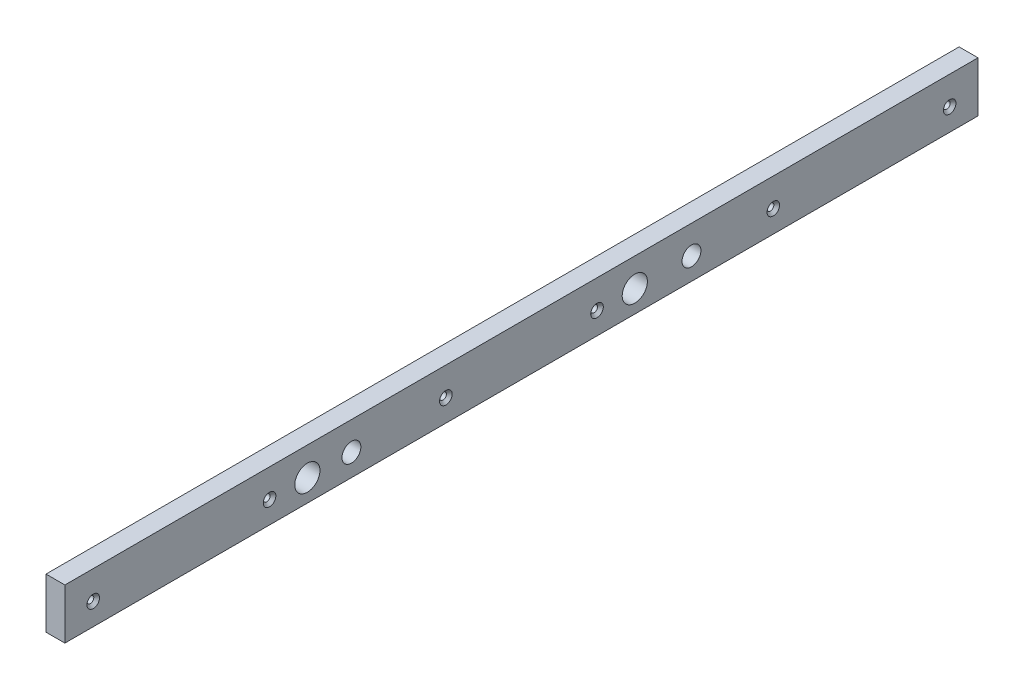
SolidWorks part; units mm, degrees
material "6061-T6 (SS)"
ref_plane "Front Plane" through (0, 0, 0) normal (0, 0, 1) x (1, 0, 0)
ref_plane "Top Plane" through (0, 0, 0) normal (0, 1, 0) x (1, 0, 0)
ref_plane "Right Plane" through (0, 0, 0) normal (1, 0, 0) x (0, 0, -1)
sketch "Sketch1" plane through (0, 0, 0) normal (0, 0, 1) x (1, 0, 0)
  line L0 (4.7625, 12.7) -> (-4.7625, -12.7) construction
  line L1 (-4.7625, 12.7) -> (4.7625, 12.7)
  line L2 (-4.7625, 12.7) -> (-4.7625, -12.7)
  line L3 (-4.7625, -12.7) -> (4.7625, -12.7)
  line L4 (4.7625, 12.7) -> (4.7625, -12.7)
  dimension "D1" = 25.4
  dimension "D2" = 9.525
extrude "Boss-Extrude1" add sketch "Sketch1" along normal mid plane 460.375
sketch "Sketch2" plane through (4.7625, 0, 0) normal (1, 0, 0) x (0, 0, -1)
  circle A1 centre (-107.95, -1.5875) radius 6.35
  circle A2 centre (57.15, -1.5875) radius 6.35
  point P0 (-25.4, -1.5875)
  dimension "D1" = 12.7
  dimension "D5" = 165.1
  dimension "D2" = 57.15
  dimension "D4" = 1.5875
  dimension "D6" = 82.55
  dimension "D7" = 25.4
extrude "Cut-Extrude1" cut sketch "Sketch2" against normal up to next
hole_wizard "3/8 (0.375) Diameter Hole1" positions "Sketch4" profile "Sketch3" hole size "3/8" standard "Ansi Inch" end condition through all
sketch "Sketch4" plane through (-4.7625, 0, 0) normal (-1, 0, 0) x (0, 0, 1)
  point P0 (85.725, -1.5875)
  point P1 (-85.725, -1.5875)
  dimension "D1" = 85.725
  dimension "D2" = 85.725
  dimension "D3" = 1.5875
sketch "Sketch3" plane through (-4.7625, -1.5875, 85.725) normal (0, 1, 0) x (0, 0, 1)
  line L0 (0, 0) -> (0, 9.525)
  line L1 (0, 9.525) -> (4.7625, 9.525)
  line L2 (4.7625, 9.525) -> (4.7625, 0)
  line L5 (4.7625, 0) -> (0, 0)
  line L11 (0, -6.35) -> (0, 107.95) construction
  dimension "Thru Hole Dia." = 9.525
  dimension "Thru Hole Depth" = 9.525
hole_wizard "#8-32 Tapped Hole1" positions "Sketch6" profile "Sketch5" tap size "#8-32" standard "Ansi Inch" end condition up to next
sketch "Sketch6" plane through (4.7625, 0, 0) normal (1, 0, 0) x (0, 0, -1)
  point P0 (215.9, -1.5875)
  point P1 (38.1, -1.5875)
  point P3 (-38.1, -1.5875)
  point P5 (-215.9, -1.5875)
  point P11 (-127, -1.5875)
  point P13 (127, -1.5875)
  dimension "D1" = 38.1
  dimension "D2" = 38.1
  dimension "D3" = 177.8
  dimension "D4" = 177.8
  dimension "D5" = 1.5875
  dimension "D6" = 88.9
  dimension "D7" = 88.9
sketch "Sketch5" plane through (4.7625, -1.5875, -215.9) normal (0, 1, 0) x (0, 0, -1)
  line L0 (0, 0) -> (0, 9.525)
  line L1 (0, 9.525) -> (2.286, 9.525)
  line L2 (1.7272, 8.9662) -> (1.7272, 1.4478)
  line L3 (1.7272, 1.4478) -> (3.175, 0)
  line L5 (3.175, 0) -> (0, 0)
  line L6 (-1.7272, 1.4478) -> (-3.175, 0) construction
  line L7 (2.286, 9.525) -> (1.7272, 8.9662)
  line L8 (-2.286, 9.525) -> (-1.7272, 8.9662) construction
  line L11 (0, -6.35) -> (0, 107.95) construction
  dimension "Thread Major Dia." = 3.4544
  dimension "Thru Tap Drill Depth" = 9.525
  dimension "Near C'Sink Dia." = 6.35
  dimension "Near C'Sink Angle" = 90
  dimension "Far C'Sink Dia." = 4.572
  dimension "Far C'Sink Angle" = 90
